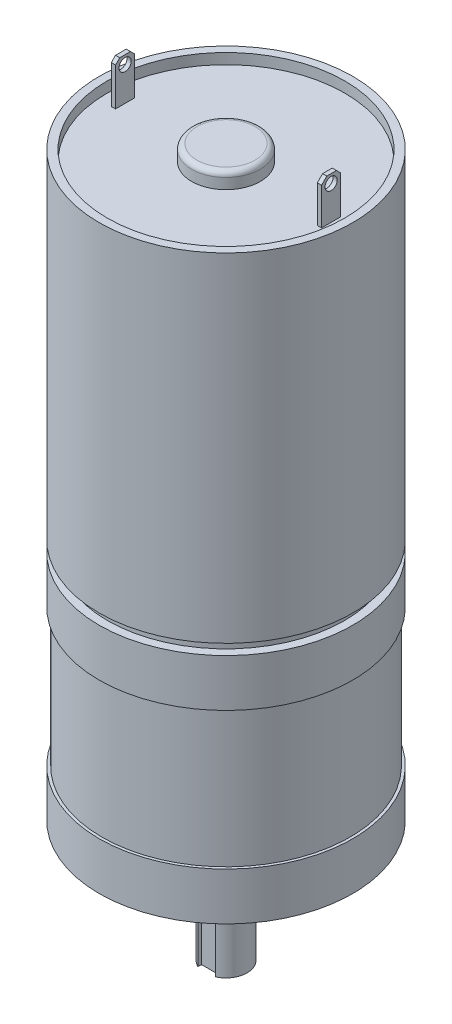
SolidWorks part; units mm, degrees
ref_plane "Front Plane" through (0, 0, 0) normal (0, 0, 1) x (1, 0, 0)
ref_plane "Top Plane" through (0, 0, 0) normal (0, 1, 0) x (1, 0, 0)
ref_plane "Right Plane" through (0, 0, 0) normal (1, 0, 0) x (0, 0, -1)
sketch "Sketch2" plane through (0, 0, 0) normal (0, 1, 0) x (1, 0, 0)
  circle A0 centre (0, 0) radius 12
  dimension "D1" = 24
extrude "Boss-Extrude1" add sketch "Sketch2" along normal mid plane 55
sketch "Sketch3" plane through (0, 27.5, 0) normal (0, 1, 0) x (1, 0, 0)
  circle A0 centre (0, 0) radius 11.2454
extrude "Cut-Extrude1" cut sketch "Sketch3" against normal blind 1
sketch "Sketch4" plane through (0, -27.5, 0) normal (0, -1, 0) x (1, 0, 0)
  circle A0 centre (0, 0) radius 12
  circle A1 centre (0, 0) radius 11.2267
extrude "Cut-Extrude2" cut sketch "Sketch4" against normal blind 1 from offset 22 offset against normal yes
sketch "Sketch5" plane through (0, -27.5, 0) normal (0, -1, 0) x (1, 0, 0)
  circle A0 centre (0, 0) radius 12
  circle A4 centre (0, 0) radius 11.7424
extrude "Cut-Extrude7" cut sketch "Sketch5" against normal mid plane 13 from offset 11 offset against normal yes
sketch "Sketch6" plane through (0, -27.5, 0) normal (0, -1, 0) x (1, 0, 0)
  circle A0 centre (0, 0) radius 3.5
  dimension "D1" = 7
extrude "Boss-Extrude2" add sketch "Sketch6" along normal blind 2.5
sketch "Sketch7" plane through (0, -30, 0) normal (0, -1, 0) x (1, 0, 0)
  circle A0 centre (0, 0) radius 2
  dimension "D1" = 4
extrude "Boss-Extrude3" add sketch "Sketch7" along normal blind 9
sketch "Sketch8" plane through (0, -39, 0) normal (0, -1, 0) x (1, 0, 0)
  line L0 (0, 0) -> (0, 2) construction
  line L1 (0, 1.6593) -> (1.6834, 1.6593) construction
  line L2 (0.8417, 1.6593) -> (0.8417, 2.2026)
  line L3 (0.8417, 2.2026) -> (-0.8417, 2.2026)
  line L4 (-0.8417, 1.6593) -> (-0.8417, 2.2026)
  line L6 (-0.8417, 1.6593) -> (-0.8417, 1.4782)
  line L7 (-0.8417, 1.4782) -> (0.8417, 1.4782)
  line L9 (0.8417, 1.4782) -> (0.8417, 1.6593)
  circle A0 centre (0, 0) radius 2 construction
  point P13 (0, 2.2026)
extrude "Cut-Extrude9" cut sketch "Sketch8" against normal blind 8
sketch "Sketch9" plane through (0, 26.5, 0) normal (0, 1, 0) x (1, 0, 0)
  circle A0 centre (0, 0) radius 3.25
  dimension "D1" = 6.5
extrude "Boss-Extrude4" add sketch "Sketch9" along normal blind 1.5
fillet "Fillet2" radius 0.5 1 edges at (0, 28, 3.25)
sketch "Sketch10" plane through (0, 26.5, 0) normal (0, 1, 0) x (1, 0, 0)
  line L0 (0, 0) -> (16.7724, 0) construction
  line L1 (9.5518, -0.9068) -> (9.5518, 0.9068)
  line L2 (9.5518, 0.9068) -> (9.951, 0.9068)
  line L3 (9.951, 0.9068) -> (9.951, -0.9068)
  line L4 (9.5518, -0.9068) -> (9.951, -0.9068)
  point P8 (9.951, 0)
  point P9 (9.5518, 0)
extrude "Boss-Extrude5" add sketch "Sketch10" along normal blind 4
chamfer "Chamfer1" distance 0.4 angle 45 1 edges at (9.7514, 30.5, -0.9068)
chamfer "Chamfer2" distance 0.5 angle 45 1 edges at (9.7514, 30.5, 0.9068)
sketch "Sketch11" plane through (9.951, 0, 0) normal (1, 0, 0) x (0, 0, -1)
  circle A0 centre (0, 29.6821) radius 0.5785
extrude "Cut-Extrude10" cut sketch "Sketch11" against normal blind 4
mirror "Mirror1" about plane through (0, 0, 0) normal (1, 0, 0) of "Boss-Extrude5"
mirror "Mirror5" about plane through (0, 0, 0) normal (1, 0, 0) of "Cut-Extrude10"
chamfer "Chamfer3" distance 0.4 angle 45 1 edges at (-9.7514, 30.5, -0.9068)
chamfer "Chamfer4" distance 0.4 angle 45 1 edges at (-9.7514, 30.5, 0.9068)
